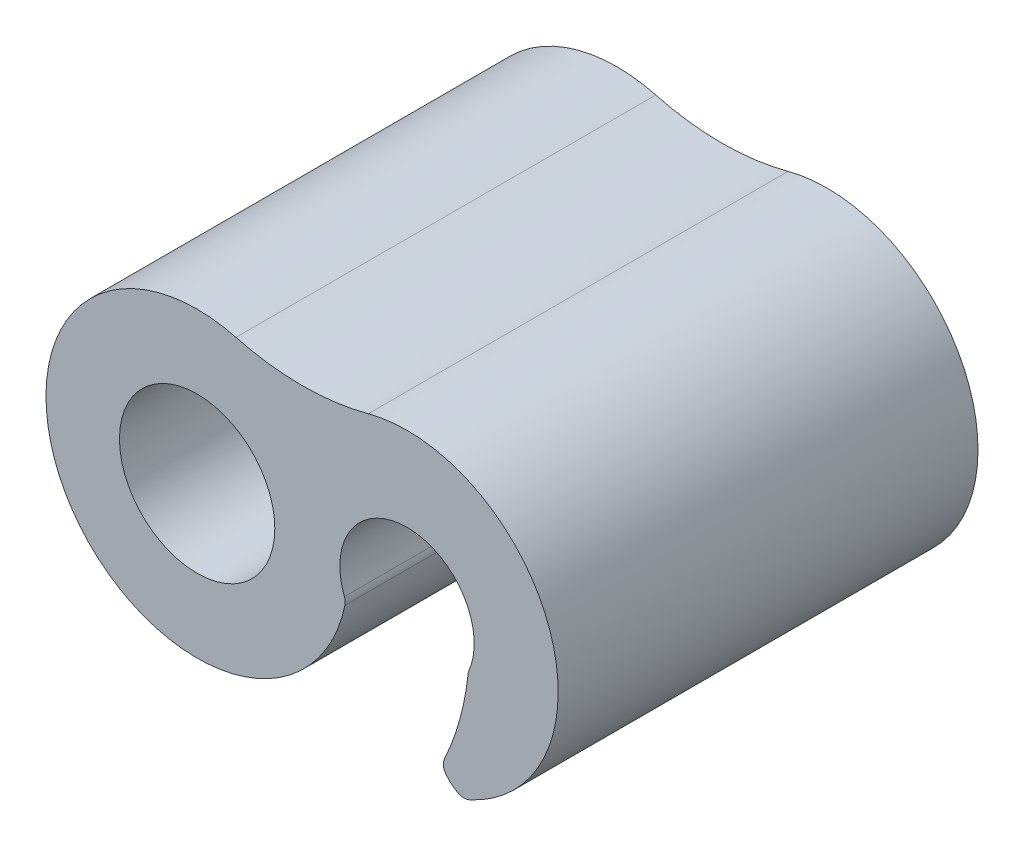
SolidWorks part; units mm, degrees
ref_plane "Front Plane" through (0, 0, 0) normal (0, 0, 1) x (1, 0, 0)
ref_plane "Top Plane" through (0, 0, 0) normal (0, 1, 0) x (1, 0, 0)
ref_plane "Right Plane" through (0, 0, 0) normal (1, 0, 0) x (0, 0, -1)
sketch "Sketch1" plane through (0, 0, 0) normal (0, 0, 1) x (1, 0, 0)
  line L0 (-2.5, 1.6545) -> (-2.5, -1.6545) construction
  line L1 (2.5, 1.5778) -> (2.5, -2.8958) construction
  line L2 (-2.5, 0) -> (2.5, 0) construction
  line L3 (0, 0) -> (0, 9.4085) construction
  line L4 (4.2, -2.4) -> (0, -2.4) construction
  line L5 (0, -2.4) -> (0, 0) construction
  arc A0 (-1.5755, 3.4793) -> (1.04, -0.6545) centre (-2.5, 0) ccw
  arc A1 (3.96, -0.6545) -> (1.04, -0.6545) centre (2.5, 0) ccw
  arc A2 (3.8507, -3.337) -> (1.5755, 3.4793) centre (2.5, 0) ccw
  circle A3 centre (-2.5, 0) radius 1.85
  arc A4 (3.321, -2.8768) -> (3.96, -0.6545) centre (-2.5, 0) ccw
  arc A5 (-1.5755, 3.4793) -> (1.5755, 3.4793) centre (0, 9.4085) ccw
  arc A6 (3.8507, -3.337) -> (3.321, -2.8768) centre (4.2, -2.4) cw
  dimension "D2" = 3.7
  dimension "D3" = 3.6
  dimension "D4" = 1
  dimension "D5" = 2.4
  dimension "D7" = 1.6
  dimension "D1" = 5
  dimension "D6" = 4.2
extrude "Boss-Extrude2" add sketch "Sketch1" along normal blind 10 contours A0 A1 A4 A2 A5
fillet "Fillet2" radius 0.3 3 edges at (3.8507, -3.337, 5) (3.321, -2.8768, 5) (1.04, -0.6545, 5)
